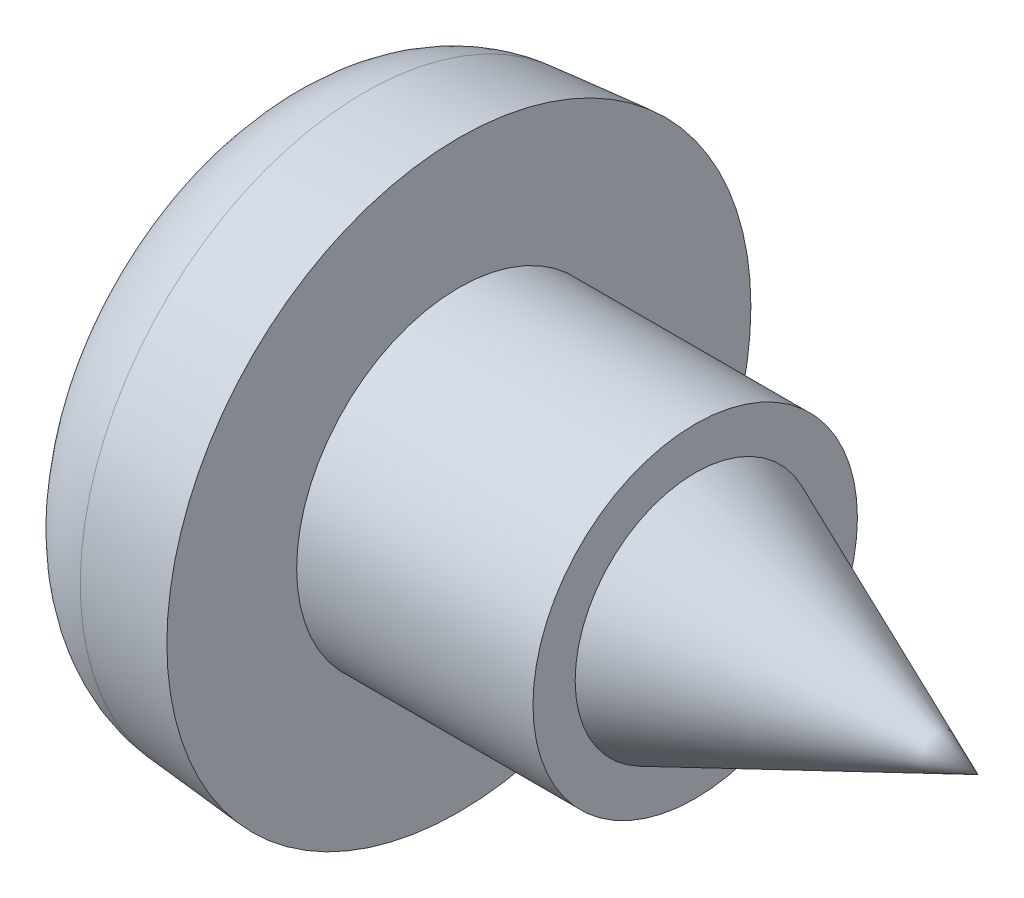
SolidWorks part; units mm, degrees
material "相当于SWCH"
ref_plane "Front Plane" through (0, 0, 0) normal (0, 0, 1) x (1, 0, 0)
ref_plane "Top Plane" through (0, 0, 0) normal (0, 1, 0) x (1, 0, 0)
ref_plane "Right Plane" through (0, 0, 0) normal (1, 0, 0) x (0, 0, -1)
sketch "Sketch1" plane through (0, 0, 0) normal (0, 0, 1) x (1, 0, 0)
  line L0 (-3.3, 0) -> (8, 0) construction
  line L1 (-1.4621, 4.3721) -> (0, 4.5)
  line L2 (0, 4.5) -> (0, 2.5)
  line L3 (0, 2.5) -> (3.6417, 2.5)
  line L4 (3.6417, 2.5) -> (3.6417, 1.85)
  line L5 (8, 0) -> (-3.3, 0)
  line L6 (-3.3, 4.5) -> (-3.3, 0) construction
  line L7 (3.6417, 1.85) -> (8, 0)
  arc A0 (-1.4621, 4.3721) -> (-2.8646, 3.205) centre (-1.3226, 2.7782) ccw
  arc A1 (-2.8646, 3.205) -> (-3.3, 0) centre (8.7143, 0) ccw
  dimension "MSM_3" = 1.6
  dimension "M" = 5
  dimension "L" = 8
  dimension "MSM_1" = 6.41
  dimension "A" = 9
  dimension "FIX_2" = 23
  dimension "MSM_2" = 3.7
  dimension "FIX_1" = 5
revolve "Revolve1" add sketch "Sketch1" angle 360 about L0
cosmetic thread "Thread1" parameters "ATD"=4.134
ref_plane "Plane1" through (-3.3, 0, 0) normal (1, 0, 0) x (0, 0, -1)
sketch "Sketch2" plane through (-3.3, 0, 0) normal (1, 0, 0) x (0, 0, -1)
  line L0 (0, 2.45) -> (0, -2.45) construction
  line L1 (2.45, 0) -> (-2.45, 0) construction
  line L4 (0.6, 1.5) -> (0.6, 2.45)
  line L5 (0.6, 2.45) -> (-0.6, 2.45)
  line L6 (-0.6, 1.5) -> (-0.6, 2.45)
  line L7 (-1.5, 0.6) -> (-2.45, 0.6)
  line L9 (-1.5, -0.6) -> (-2.45, -0.6)
  line L10 (-2.45, 0.6) -> (-2.45, -0.6)
  line L12 (0.6, -1.5) -> (0.6, -2.45)
  line L13 (0.6, -2.45) -> (-0.6, -2.45)
  line L14 (-0.6, -1.5) -> (-0.6, -2.45)
  line L15 (2.45, 0.6) -> (1.5, 0.6)
  line L16 (2.45, 0.6) -> (2.45, -0.6)
  line L17 (2.45, -0.6) -> (1.5, -0.6)
  arc A0 (0.6, -1.5) -> (1.5, -0.6) centre (1.5, -1.5) cw
  arc A1 (-1.5, -0.6) -> (-0.6, -1.5) centre (-1.5, -1.5) cw
  arc A2 (-1.5, 0.6) -> (-0.6, 1.5) centre (-1.5, 1.5) ccw
  arc A3 (0.6, 1.5) -> (1.5, 0.6) centre (1.5, 1.5) ccw
  dimension "MSM_6" = 0.9
  dimension "MSM_4" = 1.2
  dimension "MSM_5" = 4.9
extrude "Cut-Extrude1" cut sketch "Sketch2" along normal blind 1.65
